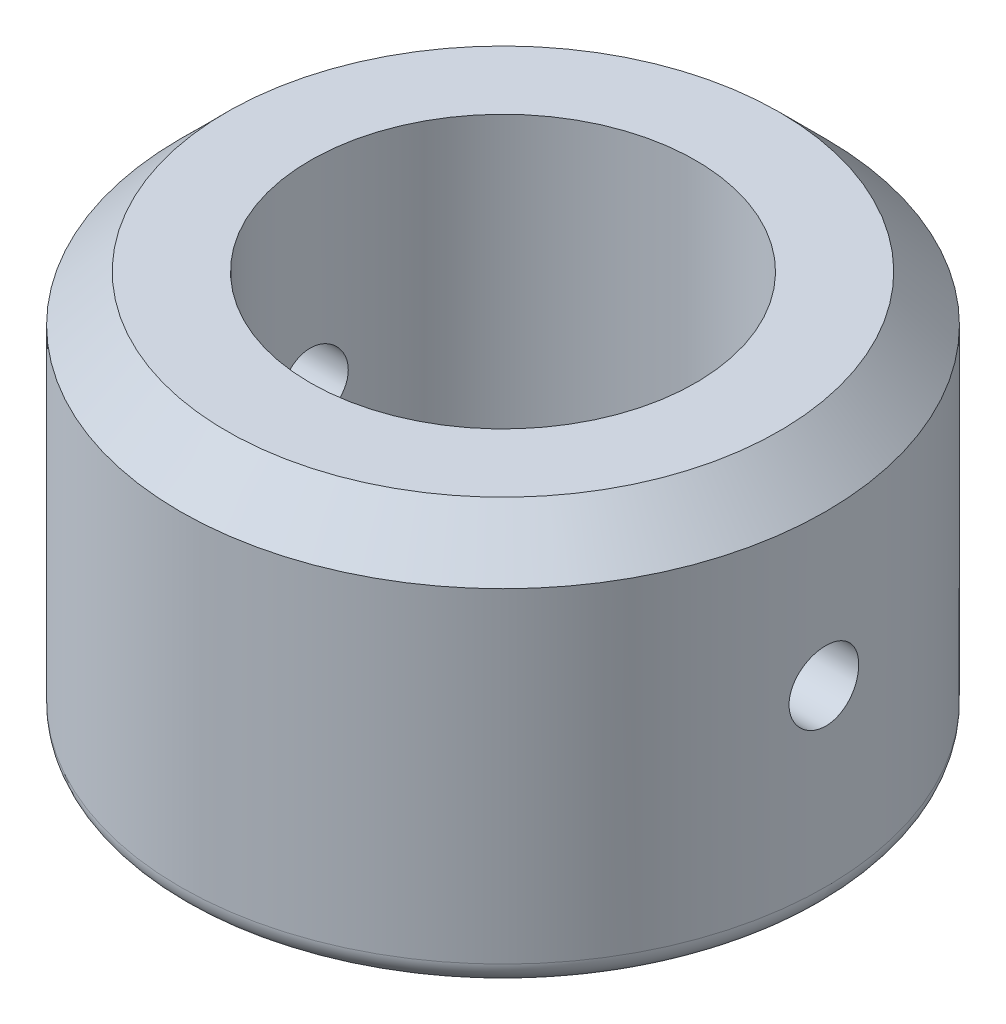
SolidWorks part; units mm, degrees
ref_plane "Front" through (0, 0, 0) normal (0, 0, 1) x (1, 0, 0)
ref_plane "Top" through (0, 0, 0) normal (0, 1, 0) x (1, 0, 0)
ref_plane "Right" through (0, 0, 0) normal (1, 0, 0) x (0, 0, -1)
sketch "Sketch1" plane through (0, 0, 0) normal (1, 0, 0) x (0, 0, -1)
  line L0 (0, 19.0132) -> (0, 0) construction
  line L1 (0, 0) -> (6.95, 0) construction
  line L3 (4.15, 4.25) -> (6.95, 4.25)
  line L4 (4.15, 4.25) -> (4.15, -4.25)
  line L5 (4.15, -4.25) -> (6.95, -4.25)
  line L6 (6.95, 4.25) -> (6.95, -4.25)
  dimension "D1" = 8.5
  dimension "D2" = 8.3
  dimension "D3" = 13.9
revolve "Revolve1" add sketch "Sketch1" angle 360 about L0
chamfer "Chamfer1" distance 1 angle 45 1 edges at (0, 4.25, 6.95)
sketch "Sketch3" plane through (0, 0, 0) normal (1, 0, 0) x (0, 0, -1)
  circle A0 centre (0, 0) radius 0.75
  dimension "D1" = 1.5
extrude "Cut-Extrude1" cut sketch "Sketch3" against normal through all both and the other way through all
fillet "Fillet1" radius 0.5 1 edges at (0, -4.25, 6.95)
